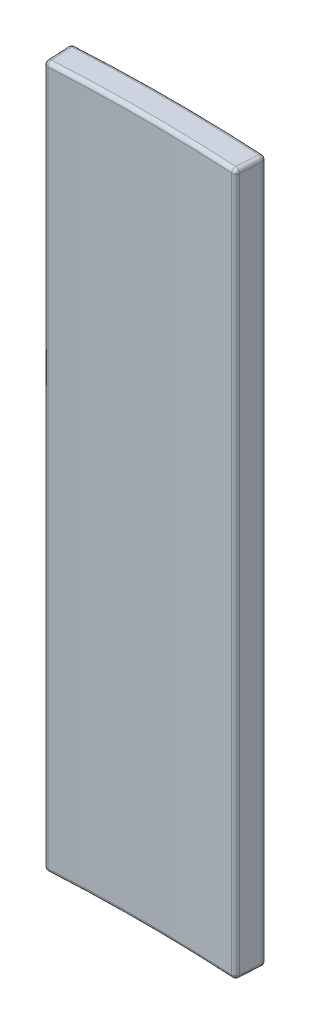
SolidWorks part; units mm, degrees
ref_plane "Horní rovina" through (0, 0, 0) normal (0, 0, 1) x (1, 0, 0)
ref_plane "Přední rovina" through (0, 0, 0) normal (0, 1, 0) x (1, 0, 0)
ref_plane "Pravá rovina" through (0, 0, 0) normal (1, 0, 0) x (0, 0, -1)
sketch "Skica1" plane through (0, 0, 0) normal (0, 1, 0) x (1, 0, 0)
  line L0 (0, 0) -> (0, 46.8261) construction
  line L43 (2.5, 42.4264) -> (0, 0) construction
  line L44 (-2.5, 42.4264) -> (0, 0) construction
  line L45 (-2.5, 42.4264) -> (-2.4559, 41.6777)
  line L46 (2.5, 42.4264) -> (2.4559, 41.6777)
  circle A0 centre (0, 0) radius 42.5 construction
  circle A1 centre (0, 0) radius 41.5 construction
  arc A2 (-2.5, 42.4264) -> (2.5, 42.4264) centre (0, 0) cw
  arc A3 (-2.4559, 41.6777) -> (2.4559, 41.6777) centre (0, 0) cw
  point P49 (0, 42.5)
  dimension "D1" = 85
  dimension "D2" = 83
  dimension "D7" = 41.75
  dimension "D6" = 5
extrude "Přidat vysunutím1" add sketch "Skica1" along normal blind 18
fillet "Zaoblit1" radius 0.1 12 edges at (-2.4779, 0, -42.0521) (-2.4559, 9, -41.6777) (0, 0, -41.75) (2.4559, 9, -41.6777) (2.4779, 0, -42.0521) (2.5, 9, -42.4264) (-2.5, 9, -42.4264) (0, 0, -42.5) (2.4779, 18, -42.0521) (0, 18, -41.75) (-2.4779, 18, -42.0521) (0, 18, -42.5)
